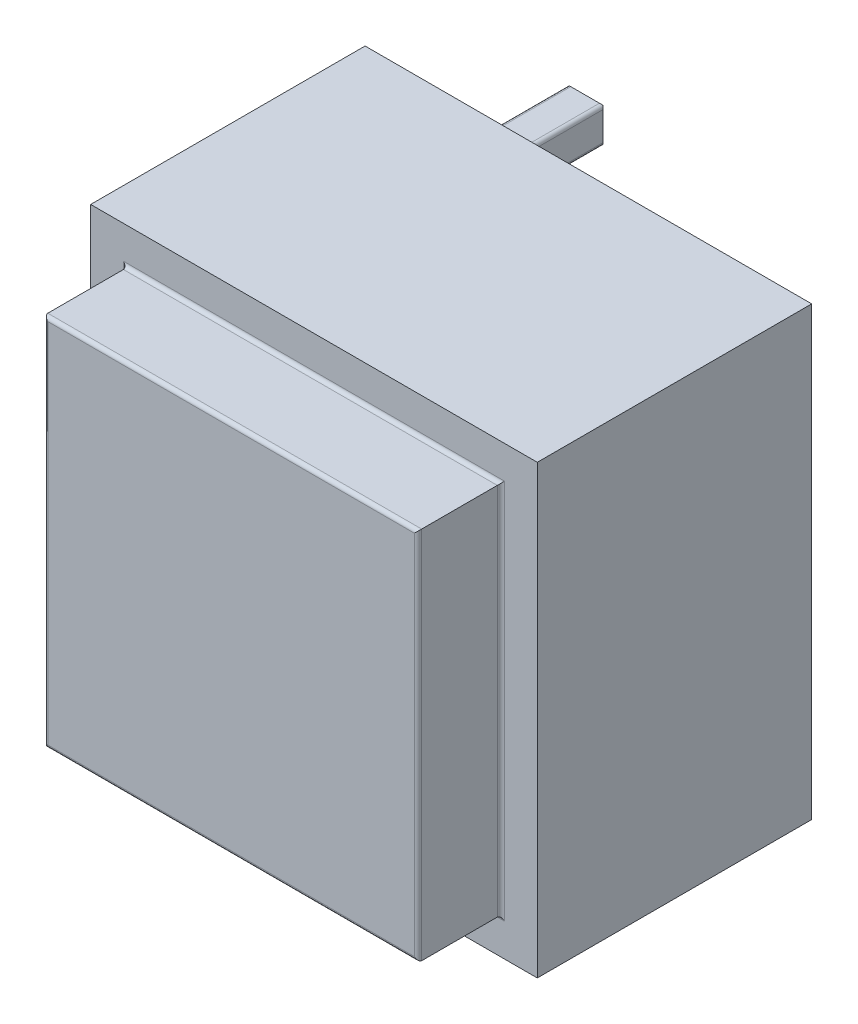
SolidWorks part; units mm, degrees
ref_plane "Front Plane" through (0, 0, 0) normal (0, 0, 1) x (1, 0, 0)
ref_plane "Top Plane" through (0, 0, 0) normal (0, 1, 0) x (1, 0, 0)
ref_plane "Right Plane" through (0, 0, 0) normal (1, 0, 0) x (0, 0, -1)
sketch "Sketch1" plane through (0, 0, 0) normal (0, 0, 1) x (1, 0, 0)
  line L1 (-6.1595, -6.1595) -> (6.1595, -6.1595)
  line L2 (-6.1595, -6.1595) -> (-6.1595, 6.1595)
  line L3 (-6.1595, 6.1595) -> (6.1595, 6.1595)
  line L4 (6.1595, -6.1595) -> (6.1595, 6.1595)
  line L5 (-6.1595, -6.1595) -> (6.1595, 6.1595) construction
  line L6 (-6.1595, 6.1595) -> (6.1595, -6.1595) construction
  point P0 (0, 0)
  dimension "D1" = 12.319
extrude "Boss-Extrude1" add sketch "Sketch1" along normal blind 7.5692
sketch "Sketch2" plane through (0, 0, 7.5692) normal (0, 0, 1) x (1, 0, 0)
  line L1 (-5.1562, -5.1562) -> (5.1562, -5.1562)
  line L2 (-5.1562, -5.1562) -> (-5.1562, 5.1562)
  line L3 (-5.1562, 5.1562) -> (5.1562, 5.1562)
  line L4 (5.1562, -5.1562) -> (5.1562, 5.1562)
  line L5 (-5.1562, -5.1562) -> (5.1562, 5.1562) construction
  line L6 (-5.1562, 5.1562) -> (5.1562, -5.1562) construction
  point P0 (0, 0)
  dimension "D1" = 10.3124
extrude "Boss-Extrude2" add sketch "Sketch2" along normal blind 2.286
sketch "Sketch3" plane through (0, 0, 0) normal (0, 0, -1) x (-1, 0, 0)
  line L0 (3.8505, 6.1595) -> (3.8505, -6.1595) construction
  line L1 (-6.1595, -6.1595) -> (6.1595, -6.1595)
  line L2 (-6.1595, -6.1595) -> (-6.1595, 6.1595)
  line L3 (-6.1595, 6.1595) -> (6.1595, 6.1595)
  line L4 (6.1595, -6.1595) -> (6.1595, 6.1595)
  line L5 (-6.1595, -6.1595) -> (6.1595, 6.1595) construction
  line L6 (-6.1595, 6.1595) -> (6.1595, -6.1595) construction
  circle A1 centre (-1.2295, 1.2295) radius 0.6096
  circle A2 centre (-3.7695, -1.3105) radius 0.6096
  point P0 (0, 0)
  point P7 (-3.7695, -1.3105)
  point P8 (-1.2295, 1.2295)
  point P9 (3.8505, 3.7695)
  point P10 (3.8505, -3.8505)
  point P14 (0, 0)
  dimension "D7" = 2.39
  dimension "D8" = 1.2192
  dimension "D9" = 1.2192
  dimension "D1" = 2.39
  dimension "D2" = 2.54
  dimension "D3" = 2.54
  dimension "D4" = 2.54
  dimension "D5" = 2.54
  dimension "D6" = 5.08
extrude "Boss-Extrude5" add sketch "Sketch3" along normal blind 1.4986 contours A1 | A2
fillet "Fillet2" radius 0.5 2 edges at (3.1599, -1.3105, -1.4986) (0.6199, 1.2295, -1.4986)
fillet "Fillet3" radius 0.1 2 edges at (0.6199, 1.2295, 0) (3.1599, -1.3105, 0)
sketch "Sketch5" plane through (0, 0, 0) normal (0, 0, -1) x (-1, 0, 0)
  line L0 (-6.1595, 6.1595) -> (6.1595, 6.1595) construction
  line L1 (-6.1595, -6.1595) -> (-6.1595, 6.1595) construction
  line L2 (3.8505, 6.1595) -> (3.8505, -6.1595) construction
  line L3 (6.1595, -6.1595) -> (-6.1595, -6.1595) construction
  line L4 (3.3552, -4.3458) -> (3.3552, -3.3552)
  line L5 (3.3552, 3.2742) -> (4.3458, 3.2742)
  line L6 (3.3552, 3.2742) -> (3.3552, 4.2648)
  line L7 (3.3552, 4.2648) -> (4.3458, 4.2648)
  line L8 (4.3458, 3.2742) -> (4.3458, 4.2648)
  line L9 (3.3552, 3.2742) -> (4.3458, 4.2648) construction
  line L10 (3.3552, 4.2648) -> (4.3458, 3.2742) construction
  line L11 (3.3552, -4.3458) -> (4.3458, -4.3458)
  line L12 (4.3458, -4.3458) -> (4.3458, -3.3552)
  line L13 (3.3552, -3.3552) -> (4.3458, -3.3552)
  circle A0 centre (-3.7695, -1.3105) radius 0.7096
  point P0 (3.8505, 3.7695)
  point P1 (3.8505, -3.8505)
  point P13 (3.8505, 3.7695)
  point P14 (-3.7695, -1.3105)
  dimension "D1" = 2.39
  dimension "D2" = 10.01
  dimension "D3" = 2.54
  dimension "D4" = 0.9906
  dimension "D5" = 2
extrude "Boss-Extrude6" add sketch "Sketch5" along normal blind 3.8608 contours L13 L4 L11 L12 | L5 L8 L7 L6
chamfer "Chamfer1" distance 0.1 angle 45 8 edges at (-3.3552, -3.8505, -3.8608) (-3.8505, -4.3458, -3.8608) (-4.3458, -3.8505, -3.8608) (-3.8505, -3.3552, -3.8608) (-3.3552, 3.7695, -3.8608) (-3.8505, 3.2742, -3.8608) (-4.3458, 3.7695, -3.8608) (-3.8505, 4.2648, -3.8608)
fillet "Fillet4" radius 0.1 8 edges at (-3.3552, 3.7695, 0) (-3.8505, 3.2742, 0) (-3.8505, 4.2648, 0) (-4.3458, 3.7695, 0) (-3.8505, -3.3552, 0) (-4.3458, -3.8505, 0) (-3.3552, -3.8505, 0) (-3.8505, -4.3458, 0)
fillet "Fillet5" radius 0.1 4 edges at (-5.1562, 0, 7.5692) (0, 5.1562, 7.5692) (5.1562, 0, 7.5692) (0, -5.1562, 7.5692)
fillet "Fillet6" radius 0.1 16 edges at (-4.3751, -3.3259, -0.0293) (-4.3751, -4.3751, -0.0293) (-3.3259, -4.3751, -0.0293) (-3.3259, -3.3259, -0.0293) (-3.3259, 3.2449, -0.0293) (-3.3259, 4.2941, -0.0293) (-4.3751, 3.2449, -0.0293) (-4.3751, 4.2941, -0.0293) (-4.3458, -3.3552, -1.9304) (-4.3458, -4.3458, -1.9304) (-3.3552, -4.3458, -1.9304) (-3.3552, -3.3552, -1.9304) (-3.3552, 3.2742, -1.9304) (-3.3552, 4.2648, -1.9304) (-4.3458, 3.2742, -1.9304) (-4.3458, 4.2648, -1.9304)
fillet "Fillet7" radius 0.1 4 edges at (5.1562, 0, 9.8552) (0, 5.1562, 9.8552) (-5.1562, 0, 9.8552) (0, -5.1562, 9.8552)
